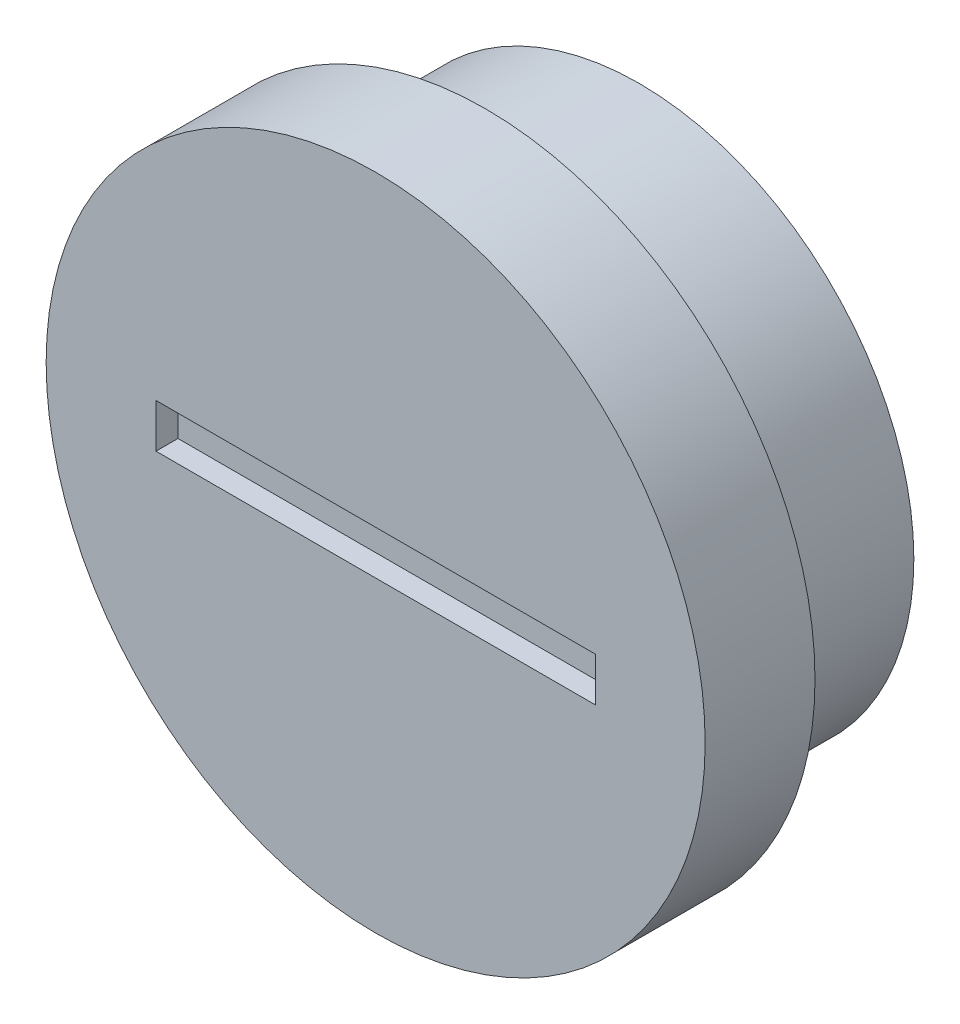
SolidWorks part; units mm, degrees
ref_plane "정면" through (0, 0, 0) normal (0, 0, 1) x (1, 0, 0)
ref_plane "윗면" through (0, 0, 0) normal (0, 1, 0) x (1, 0, 0)
ref_plane "우측면" through (0, 0, 0) normal (1, 0, 0) x (0, 0, -1)
sketch "스케치1" plane through (0, 0, 0) normal (0, 0, 1) x (1, 0, 0)
  circle A0 centre (0, 0) radius 10.65
  circle A1 centre (0, 0) radius 12.5
  dimension "D1" = 21.3
  dimension "D2" = 25
extrude "보스-돌출1" add sketch "스케치1" along normal blind 7
sketch "스케치2" plane through (0, 0, 7) normal (0, 0, 1) x (1, 0, 0)
  circle A0 centre (0, 0) radius 15
  dimension "D1" = 30
extrude "보스-돌출2" add sketch "스케치2" along normal blind 5
sketch "스케치4" plane through (0, 0, 7) normal (0, 0, -1) x (-1, 0, 0)
  circle A0 centre (0, 0) radius 9
  dimension "D1" = 18
extrude "보스-돌출3" add sketch "스케치4" along normal blind 7.5
sketch "스케치5" plane through (0, 0, 12) normal (0, 0, 1) x (1, 0, 0)
  line L1 (-10, -1) -> (10, -1)
  line L2 (-10, -1) -> (-10, 1)
  line L3 (-10, 1) -> (10, 1)
  line L4 (10, -1) -> (10, 1)
  line L5 (-10, -1) -> (10, 1) construction
  line L6 (-10, 1) -> (10, -1) construction
  point P0 (0, 0)
  dimension "D1" = 2
  dimension "D2" = 20
extrude "컷-돌출1" cut sketch "스케치5" against normal blind 1
sketch "스케치6" plane through (0, 0, -0.5) normal (0, 0, -1) x (-1, 0, 0)
  line L0 (0, 0) -> (0, 1) construction
  line L2 (-2.5, 2) -> (2.5, 2)
  line L3 (-2.5, 2) -> (-2.5, 0)
  line L4 (-2.5, 0) -> (2.5, 0)
  line L5 (2.5, 2) -> (2.5, 0)
  line L6 (-2.5, 2) -> (2.5, 0) construction
  line L7 (-2.5, 0) -> (2.5, 2) construction
  dimension "D1" = 2
  dimension "D2" = 5
extrude "컷-돌출2" cut sketch "스케치6" against normal blind 3
